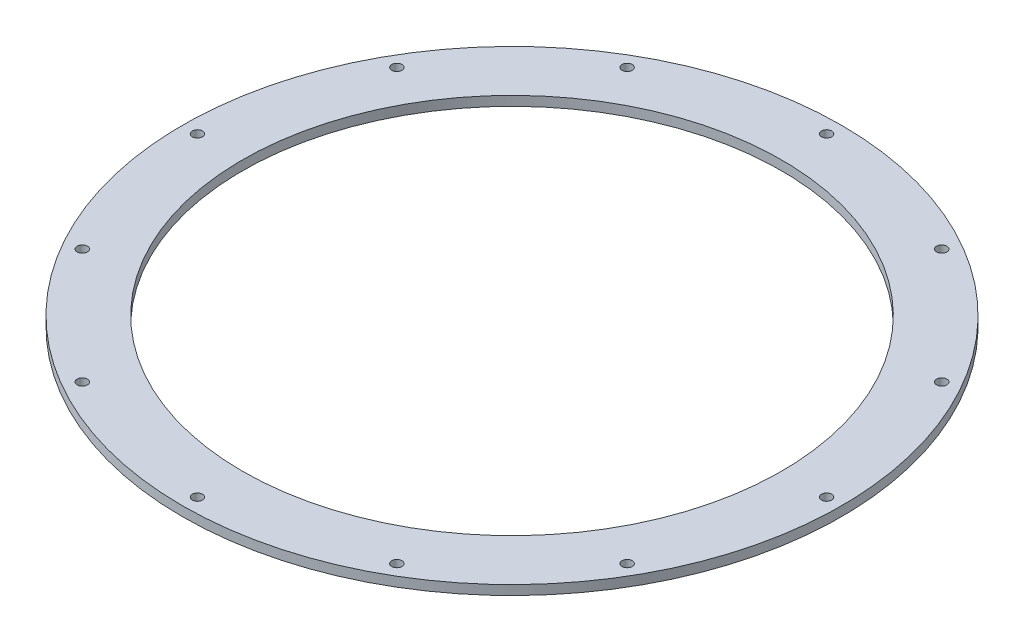
SolidWorks part; units mm, degrees
material "AISI 304"
ref_plane "Front" through (0, 0, 0) normal (0, 0, 1) x (1, 0, 0)
ref_plane "Top" through (0, 0, 0) normal (0, 1, 0) x (1, 0, 0)
ref_plane "Right" through (0, 0, 0) normal (1, 0, 0) x (0, 0, -1)
sketch "Sketch1" plane through (0, 0, 0) normal (0, 1, 0) x (1, 0, 0)
  circle A0 centre (0, 0) radius 90
  circle A1 centre (0, 0) radius 110
  dimension "D1" = 180
  dimension "D2" = 220
extrude "Boss-Extrude1" add sketch "Sketch1" along normal blind 3.175
hole_wizard "M3 Clearance Hole1" positions "Sketch2" profile "Sketch3" hole size "M3" standard "ANSI Metric" end condition up to next
sketch "Sketch2" plane through (0, 3.175, 0) normal (0, 1, 0) x (1, 0, 0)
  line L0 (0, 0) -> (0, 105) construction
  point P0 (0, 105)
  point P5 (52.5, 90.9327)
  point P6 (90.9327, 52.5)
  point P7 (105, 0)
  point P8 (90.9327, -52.5)
  point P9 (52.5, -90.9327)
  point P10 (0, -105)
  point P11 (-52.5, -90.9327)
  point P12 (-90.9327, -52.5)
  point P13 (-105, 0)
  point P14 (-90.9327, 52.5)
  point P15 (-52.5, 90.9327)
  point P18 (106.5668, 96.1483)
  point P19 (0, 0)
  dimension "D2" = 105
  dimension "D1" = 12
sketch "Sketch3" plane through (0, 3.175, -105) normal (1, 0, 0) x (0, 0, 1)
  line L0 (0, 0) -> (0, 3.175)
  line L1 (0, 3.175) -> (1.7, 3.175)
  line L2 (1.7, 3.175) -> (1.7, 0)
  line L5 (1.7, 0) -> (0, 0)
  line L11 (0, -6.35) -> (0, 107.95) construction
  dimension "Thru Hole Dia." = 3.4
  dimension "Thru Hole Depth" = 3.175
